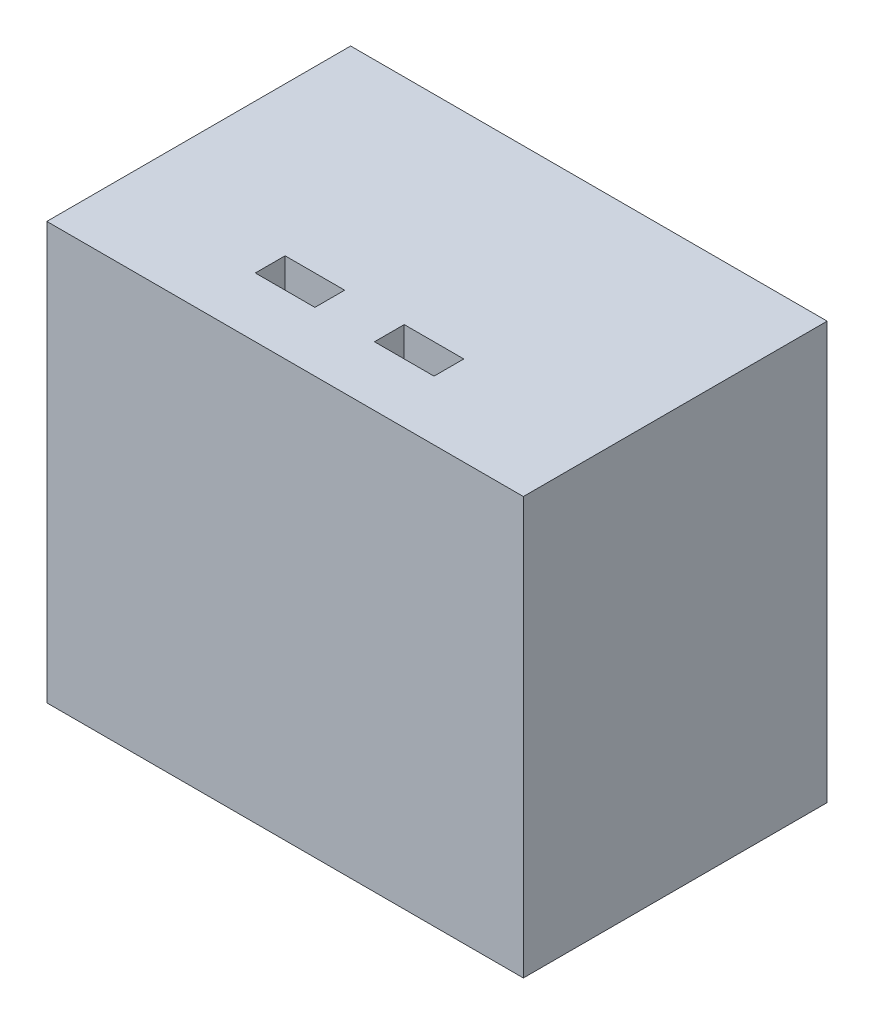
SolidWorks part; units mm, degrees
ref_plane "Front Plane" through (0, 0, 0) normal (0, 0, 1) x (1, 0, 0)
ref_plane "Top Plane" through (0, 0, 0) normal (0, 1, 0) x (1, 0, 0)
ref_plane "Right Plane" through (0, 0, 0) normal (1, 0, 0) x (0, 0, -1)
sketch "Sketch2" plane through (0, 0, 0) normal (0, 0, 1) x (1, 0, 0)
  line L1 (-40, -35) -> (40, -35)
  line L2 (-40, -35) -> (-40, 35)
  line L3 (-40, 35) -> (40, 35)
  line L4 (40, -35) -> (40, 35)
  line L5 (-40, -35) -> (40, 35) construction
  line L6 (-40, 35) -> (40, -35) construction
  point P0 (0, 0)
  dimension "D1" = 80
  dimension "D2" = 70
extrude "Boss-Extrude1" add sketch "Sketch2" along normal blind 51
sketch "Sketch3" plane through (0, 35, 0) normal (0, 1, 0) x (1, 0, 0)
  line L0 (0, 0) -> (0, -51) construction
  line L1 (-15, -41) -> (-5, -41)
  line L2 (-15, -41) -> (-15, -36)
  line L3 (-15, -36) -> (-5, -36)
  line L4 (-5, -41) -> (-5, -36)
  line L5 (-15, -41) -> (-5, -36) construction
  line L6 (-15, -36) -> (-5, -41) construction
  line L7 (40, 0) -> (-40, 0) construction
  line L8 (40, -51) -> (-40, -51) construction
  line L9 (15, -36) -> (5, -36)
  line L10 (5, -41) -> (5, -36)
  line L11 (15, -41) -> (5, -41)
  line L12 (15, -41) -> (15, -36)
  point P0 (-10, -38.5)
  dimension "D1" = 10
  dimension "D2" = 5
  dimension "D3" = 10
  dimension "D4" = 10
extrude "Cut-Extrude1" cut sketch "Sketch3" against normal blind 10
